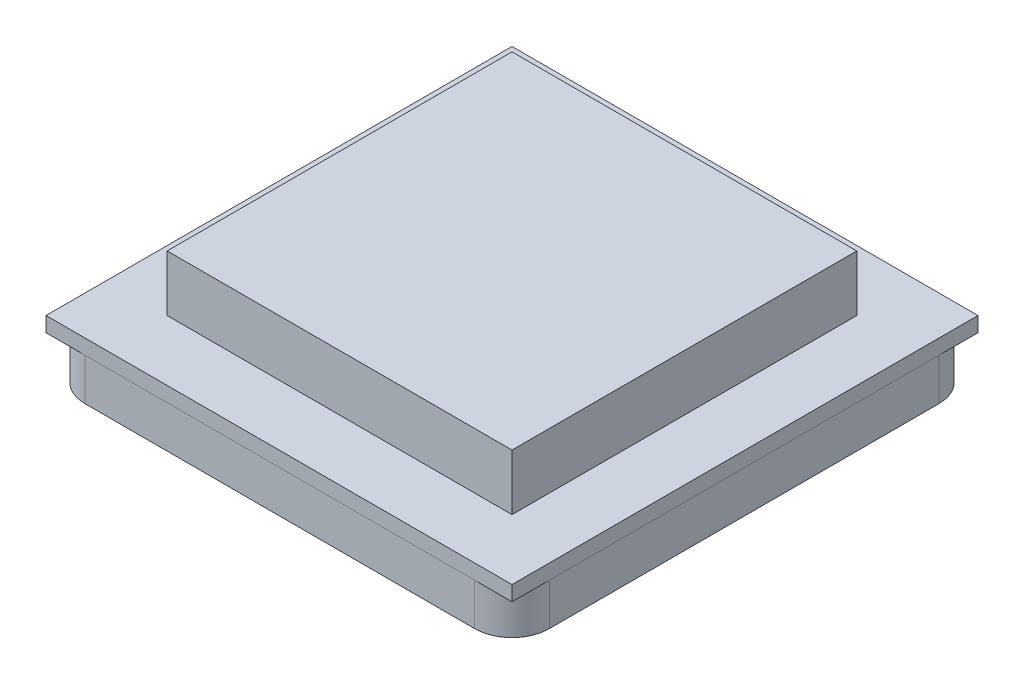
SolidWorks part; units mm, degrees
ref_plane "Front Plane" through (0, 0, 0) normal (0, 0, 1) x (1, 0, 0)
ref_plane "Top Plane" through (0, 0, 0) normal (0, 1, 0) x (1, 0, 0)
ref_plane "Right Plane" through (0, 0, 0) normal (1, 0, 0) x (0, 0, -1)
sketch "Sketch1" plane through (0, 0, 0) normal (0, 1, 0) x (1, 0, 0)
  line L1 (-12.5, -12.5) -> (12.5, -12.5)
  line L2 (-12.5, -12.5) -> (-12.5, 12.5)
  line L3 (-12.5, 12.5) -> (12.5, 12.5)
  line L4 (12.5, -12.5) -> (12.5, 12.5)
  line L5 (-12.5, -12.5) -> (12.5, 12.5) construction
  line L6 (-12.5, 12.5) -> (12.5, -12.5) construction
  point P0 (0, 0)
  dimension "D1" = 25
  dimension "D2" = 25
extrude "Boss-Extrude1" add sketch "Sketch1" along normal blind 0.8
sketch "Sketch2" plane through (0, 0.8, 0) normal (0, 1, 0) x (1, 0, 0)
  line L1 (-9.25, -9.25) -> (9.25, -9.25)
  line L2 (-9.25, -9.25) -> (-9.25, 9.25)
  line L3 (-9.25, 9.25) -> (9.25, 9.25)
  line L4 (9.25, -9.25) -> (9.25, 9.25)
  line L5 (-9.25, -9.25) -> (9.25, 9.25) construction
  line L6 (-9.25, 9.25) -> (9.25, -9.25) construction
  point P0 (0, 0)
  dimension "D1" = 18.5
  dimension "D2" = 18.5
extrude "Boss-Extrude2" add sketch "Sketch2" along normal blind 3
sketch "Sketch3" plane through (0, 0, 0) normal (0, -1, 0) x (1, 0, 0)
  line L1 (-10.45, -12.45) -> (10.45, -12.45)
  line L2 (-12.45, -10.45) -> (-12.45, 10.45)
  line L3 (-10.45, 12.45) -> (10.45, 12.45)
  line L4 (12.45, -10.45) -> (12.45, 10.45)
  line L5 (-12.45, -12.45) -> (12.45, 12.45) construction
  line L6 (-12.45, 12.45) -> (12.45, -12.45) construction
  arc A0 (-10.45, -12.45) -> (-12.45, -10.45) centre (-10.45, -10.45) cw
  arc A1 (10.45, -12.45) -> (12.45, -10.45) centre (10.45, -10.45) ccw
  arc A2 (10.45, 12.45) -> (12.45, 10.45) centre (10.45, 10.45) cw
  arc A3 (-12.45, 10.45) -> (-10.45, 12.45) centre (-10.45, 10.45) cw
  point P0 (0, 0)
  dimension "D3" = 2
  dimension "D1" = 24.9
  dimension "D2" = 24.9
extrude "Boss-Extrude4" add sketch "Sketch3" along normal blind 2.3
